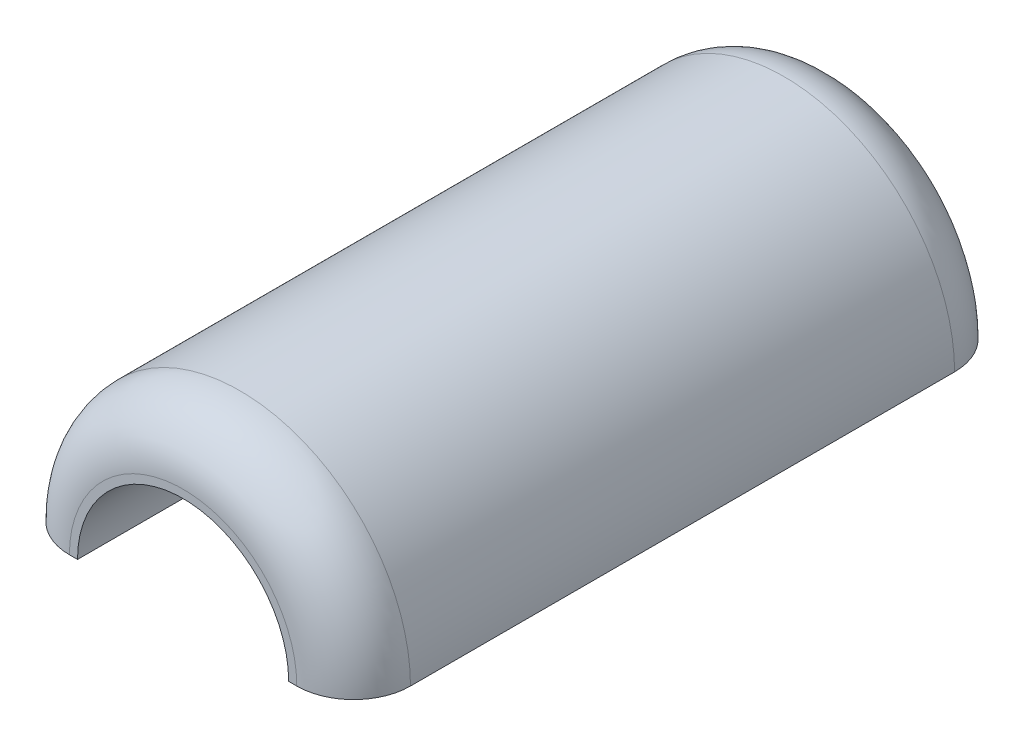
SolidWorks part; units mm, degrees
ref_plane "Front Plane" through (0, 0, 0) normal (0, 0, 1) x (1, 0, 0)
ref_plane "Top Plane" through (0, 0, 0) normal (0, 1, 0) x (1, 0, 0)
ref_plane "Right Plane" through (0, 0, 0) normal (1, 0, 0) x (0, 0, -1)
sketch "Sketch1" plane through (0, 0, 0) normal (0, 0, 1) x (1, 0, 0)
  circle A0 centre (0, 0) radius 10.5
extrude "Boss-Extrude1" add sketch "Sketch1" along normal blind 40.5
shell "Shell1" thickness 4
fillet "Fillet1" radius 3.5 1 edges at (10.5, 0, 40.5)
fillet "Fillet2" radius 3.5 1 edges at (10.5, 0, 0)
fillet "Fillet3" radius 1 1 edges at (6.5, 0, 4)
sketch "Sketch2" plane through (0, 0, 0) normal (0, 1, 0) x (1, 0, 0)
  line L1 (-17.9548, 9.1145) -> (19.6353, 9.1145)
  line L2 (-17.9548, 9.1145) -> (-17.9548, -45.6344)
  line L3 (-17.9548, -45.6344) -> (19.6353, -45.6344)
  line L4 (19.6353, 9.1145) -> (19.6353, -45.6344)
extrude "Cut-Extrude1" cut sketch "Sketch2" against normal blind 40.5
